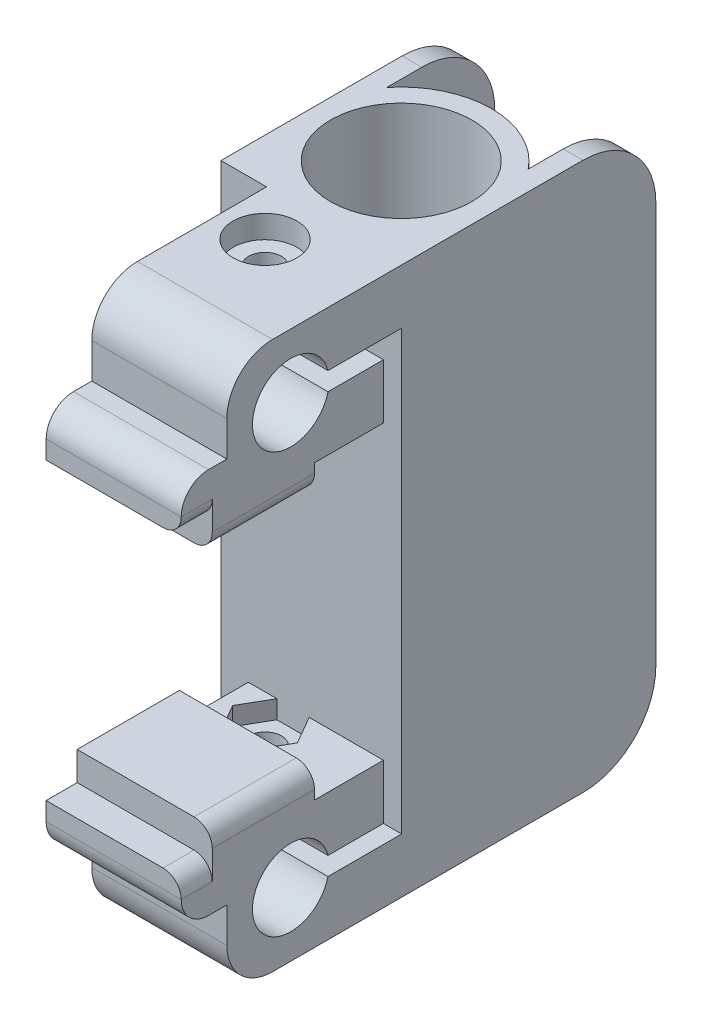
SolidWorks part; units mm, degrees
ref_plane "Спереди" through (0, 0, 0) normal (0, 0, 1) x (1, 0, 0)
ref_plane "Сверху" through (0, 0, 0) normal (0, 1, 0) x (1, 0, 0)
ref_plane "Справа" through (0, 0, 0) normal (1, 0, 0) x (0, 0, -1)
sketch "Эскиз1" plane through (0, 0, 0) normal (0, 1, 0) x (1, 0, 0)
  line L0 (9.9, 0) -> (9.9, 18)
  line L1 (9.9, 18) -> (-9.9, 18)
  line L2 (-9.9, 18) -> (-9.9, 0)
  line L3 (-9.9, 0) -> (-9.9, -29)
  line L4 (-9.9, -29) -> (9.9, -29)
  line L5 (9.9, -29) -> (9.9, 0)
  line L7 (-7.75, -23.1528) -> (7.75, -23.1528)
  line L8 (-7.75, -23.1528) -> (-7.75, 14)
  line L9 (-7.75, 14) -> (7.75, 14)
  line L10 (7.75, -23.1528) -> (7.75, 14)
  line L11 (-7.75, -9.9) -> (7.75, -9.9)
  line L12 (-7.75, -9.9) -> (-7.75, -11.85)
  line L13 (-7.75, -11.85) -> (7.75, -11.85)
  line L14 (7.75, -9.9) -> (7.75, -11.85)
  circle A0 centre (0, 0) radius 7.75
  circle A2 centre (0, 0) radius 9.9
  point P18 (0, -9.9)
  dimension "D1" = 15.5
  dimension "D2" = 19.8
  dimension "D4" = 2.15
  dimension "D3" = 18
  dimension "D5" = 1.95
  dimension "D6" = 47
  dimension "D7" = 4
extrude "Бобышка-Вытянуть1" add sketch "Эскиз1" along normal blind 60 contours L10 A2 L8 A0 | A2 L0 L1 L2 L8 L9 L10 | L10 A2 | L8 A2 | A2 L10 A0 L8 | A2 L10 L7 L8 L3 L4 L5 | L13 L8 L7 L10 | L8 L13 L10 L11 | A2 L11 L10 | A2 L8 L11
sketch "Эскиз2" plane through (9.9, 0, 0) normal (1, 0, 0) x (0, 0, -1)
  line L0 (-29, 60) -> (-29, 0) construction
  line L1 (-29, 60) -> (18, 60) construction
  line L2 (-29, 0) -> (18, 0) construction
  circle A0 centre (-22, 53) radius 4.2
  circle A1 centre (-22, 7) radius 4.2
  dimension "D1" = 8.4
  dimension "D2" = 7
  dimension "D3" = 7
  dimension "D4" = 7
extrude "Вырез-Вытянуть1" cut sketch "Эскиз2" against normal blind 90
sketch "Эскиз3" plane through (9.9, 0, 0) normal (1, 0, 0) x (0, 0, -1)
  line L1 (-29, 60) -> (-29, 0) construction
  line L2 (-29, 0) -> (18, 0) construction
  line L3 (-29, 60) -> (18, 60) construction
  line L5 (-33.0715, 30) -> (18, 30) construction
  line L10 (18, 60) -> (18, 0) construction
  line L26 (-22, 6) -> (-9.85, 6)
  line L27 (-22, 6) -> (-22, 8)
  line L28 (-22, 8) -> (-9.85, 8)
  line L29 (-9.85, 6) -> (-9.85, 8)
  line L30 (-22, 52) -> (-9.85, 52)
  line L31 (-22, 52) -> (-22, 54)
  line L32 (-22, 54) -> (-9.85, 54)
  line L33 (-9.85, 52) -> (-9.85, 54)
  line L34 (-9.85, 6) -> (-11.85, 6)
  line L35 (-9.85, 6) -> (-9.85, 54)
  line L36 (-9.85, 54) -> (-11.85, 54)
  line L37 (-11.85, 6) -> (-11.85, 54)
  line L38 (-9.85, 14) -> (-29, 14)
  line L39 (-9.85, 14) -> (-9.85, 46)
  line L40 (-9.85, 46) -> (-29, 46)
  line L41 (-29, 14) -> (-29, 46)
  circle A1 centre (-22, 7) radius 4.2 construction
  circle A2 centre (-22, 53) radius 4.2 construction
  point P2 (-22, 7)
  point P7 (-22, 53)
  dimension "D2" = 14
  dimension "D3" = 14
  dimension "D4" = 17.15
  dimension "D8" = 2
  dimension "D9" = 2
  dimension "D10" = 2
extrude "Вырез-Вытянуть2" cut sketch "Эскиз3" against normal blind 40
sketch "Эскиз4" plane through (0, 0, -18) normal (0, 0, -1) x (-1, 0, 0)
  line L0 (-9.9, 60) -> (9.9, 60) construction
  line L1 (-7.75, 60) -> (7.75, 60)
  line L2 (-7.75, 60) -> (-7.75, 40.5)
  line L3 (-7.75, 26.5) -> (7.75, 26.5)
  line L4 (7.75, 60) -> (7.75, 40.5)
  line L5 (-9.9, 0) -> (9.9, 0) construction
  line L6 (7.75, 26.5) -> (7.75, 33.5)
  line L7 (7.75, 33.5) -> (-7.75, 33.5)
  line L9 (7.75, 40.5) -> (-7.75, 40.5)
  line L10 (-7.75, 0) -> (7.75, 0)
  line L11 (-7.75, 0) -> (-7.75, 19.5)
  line L12 (-7.75, 19.5) -> (7.75, 19.5)
  line L13 (7.75, 0) -> (7.75, 19.5)
  line L14 (7.75, 26.5) -> (7.75, 33.5)
  line L15 (-7.75, 60) -> (-7.75, 40.5)
  line L16 (7.75, 40.5) -> (7.75, 60)
  line L17 (-7.75, 33.5) -> (-7.75, 26.5)
  line L18 (-7.75, 33.5) -> (-7.75, 26.5)
  line L19 (7.75, 33.5) -> (7.75, 26.5)
  line L20 (9.9, 60) -> (9.9, 0) construction
  point P20 (7.75, 30)
  point P23 (9.9, 30)
  line M9 (-9.9, 0) -> (9.9, 0)
  line M11 (9.9, 60) -> (-9.9, 60)
  dimension "D1" = 7
  dimension "D2" = 7
  dimension "D4" = 7
extrude "Вырез-Вытянуть3" cut sketch "Эскиз4" against normal blind 6 contours L4 L2 L3 M11 | L13 L12 L11 M9 | L7 L17 L3 L6
fillet "Скругление1" radius 5 2 edges at (0, 60, 29) (0, 0, 29)
fillet "Скругление2" radius 8 4 edges at (8.825, 60, -18) (8.825, 0, -18) (-8.825, 0, -18) (-8.825, 60, -18)
sketch "Эскиз13" plane through (0, 0, 0) normal (0, -1, 0) x (1, 0, 0)
  circle A0 centre (0, 14.9208) radius 1.8
  dimension "D1" = 3.6
  dimension "D2" = 3
extrude "Вырез-Вытянуть9" cut sketch "Эскиз13" against normal blind 75
sketch "Эскиз14" plane through (0, 14, 0) normal (0, 1, 0) x (1, 0, 0)
  line L0 (-9.9, -11.85) -> (9.9, -11.85) construction
  line L1 (-1.7729, -17.9916) -> (1.7729, -17.9916)
  line L2 (1.7729, -17.9916) -> (3.5458, -14.9208)
  line L3 (3.5458, -14.9208) -> (1.7729, -11.85)
  line L4 (1.7729, -11.85) -> (-1.7729, -11.85)
  line L5 (-1.7729, -11.85) -> (-3.5458, -14.9208)
  line L6 (-3.5458, -14.9208) -> (-1.7729, -17.9916)
  circle A0 centre (0, -14.9208) radius 3.0708 construction
extrude "Вырез-Вытянуть10" cut sketch "Эскиз14" against normal blind 2 and the other way blind 34
sketch "Эскиз15" plane through (0, 60, 0) normal (0, 1, 0) x (1, 0, 0)
  circle A0 centre (0, -14.9208) radius 3.5
  dimension "D1" = 7
extrude "Вырез-Вытянуть11" cut sketch "Эскиз15" against normal blind 2.5
sketch "Эскиз16" plane through (0, 0, 0) normal (0, -1, 0) x (1, 0, 0)
  circle A0 centre (0, 14.9208) radius 3.5
  dimension "D1" = 7
extrude "Вырез-Вытянуть12" cut sketch "Эскиз16" against normal blind 2.5
sketch "Эскиз17" plane through (9.9, 0, 0) normal (1, 0, 0) x (0, 0, -1)
  line L0 (-11.85, 14) -> (-29, 14) construction
  line L1 (-19.4, 14) -> (-29, 14)
  line L2 (-19.4, 14) -> (-19.4, 17)
  line L3 (-19.4, 17) -> (-30.6, 17)
  line L4 (-30.6, 13.85) -> (-30.6, 17)
  line L5 (-29, 14) -> (-29, 5) construction
  line L6 (-30.6, 17) -> (-28.4627, 17)
  line L7 (-30.6, 17) -> (-30.6, 13.85)
  line L8 (-29.8084, 8.85) -> (-29, 8.85)
  line L9 (-29, 14) -> (-29, 8.85)
  line L10 (-34, 14.25) -> (-31, 14.25) construction
  line L11 (-29, 8.85) -> (-34, 8.85)
  line L12 (-29, 8.85) -> (-29, 14)
  line L13 (-30.6, 13.85) -> (-34, 13.85)
  line L14 (-34, 8.85) -> (-34, 13.85)
  line L15 (-31, 14.25) -> (-31, 45.75) construction
  line L16 (-19, 45.75) -> (-19, 14.25) construction
  line L17 (-34, 45.75) -> (-34, 14.25) construction
  line L18 (-59.9355, 30) -> (-24.4779, 30) construction
  line L19 (-9.85, 6) -> (-9.85, 54) construction
  line L20 (-19.4, 43) -> (-30.6, 43)
  line L21 (-19.4, 46) -> (-19.4, 43)
  line L22 (-19.4, 46) -> (-29, 46)
  line L23 (-29, 46) -> (-29, 51.15)
  line L24 (-30.6, 46.15) -> (-30.6, 43)
  line L25 (-30.6, 46.15) -> (-34, 46.15)
  line L26 (-34, 51.15) -> (-34, 46.15)
  line L27 (-29, 51.15) -> (-34, 51.15)
  point P26 (-9.85, 30)
  line M14 (-29, 55) -> (-29, 46)
  line M15 (-29, 46) -> (-11.85, 46)
  line M25 (-11.85, 14) -> (-29, 14)
  line M26 (-29, 14) -> (-29, 5)
  dimension "D1" = 5
  dimension "D2" = 0.4
  dimension "D3" = 0.4
  dimension "D4" = 0.4
  dimension "D5" = 3
extrude "Бобышка-Вытянуть2" add sketch "Эскиз17" against normal up to vertex (19.8 mm away) contours L27 L26 L25 L24 L20 L21 M14 M15 | L14 L11 L8 L2 L3 L4 L13 M26 M25 up to point (-9.9, 14, 29)
fillet "Скругление3" radius 3 2 edges at (0, 51.15, 34) (0, 8.85, 34)
sketch "Эскиз18" plane through (-9.9, 0, 0) normal (-1, 0, 0) x (0, 0, 1)
  circle A0 centre (25, 14) radius 2.25
  circle A1 centre (25, 46) radius 2.25
  circle A2 centre (25, 14) radius 1.5 construction
  circle A3 centre (25, 46) radius 1.5 construction
  dimension "D1" = 4.5
extrude "Вырез-Вытянуть13" cut sketch "Эскиз18" against normal blind 9
fillet "Скругление4" radius 2 4 edges at (9.9, 13.85, 32.3) (9.9, 17, 25) (9.9, 43, 25) (9.9, 46.15, 32.3)
sketch "Эскиз19" plane through (-9.9, 0, 0) normal (-1, 0, 0) x (0, 0, 1)
  line L0 (9.85, 6) -> (9.85, 54) construction
  line L1 (9.85, 64.1157) -> (50.8214, 64.1157)
  line L2 (9.85, 64.1157) -> (9.85, -14.7812)
  line L3 (9.85, -14.7812) -> (50.8214, -14.7812)
  line L4 (50.8214, 64.1157) -> (50.8214, -14.7812)
extrude "Вырез-Вытянуть14" cut sketch "Эскиз19" against normal blind 5
